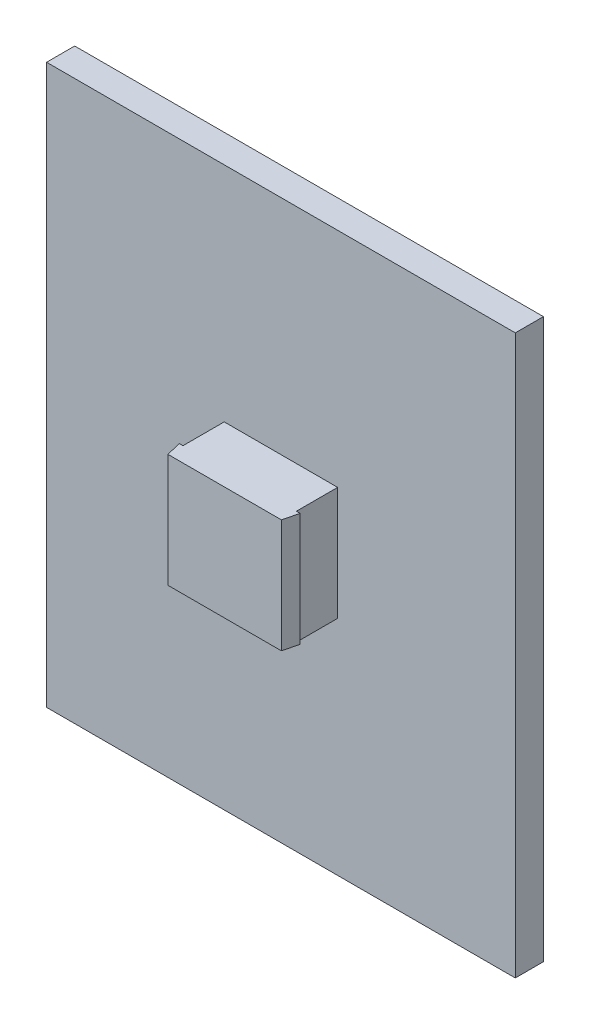
SolidWorks part; units mm, degrees
ref_plane "Front Plane" through (0, 0, 0) normal (1, 0, 0) x (0, 1, 0)
ref_plane "Top Plane" through (0, 0, 0) normal (0, 0, 1) x (0, 1, 0)
ref_plane "Right Plane" through (0, 0, 0) normal (0, 1, 0) x (-1, 0, 0)
sketch "Sketch2" plane through (0, 0, 0) normal (0, 0, 1) x (0, 1, 0)
  line L1 (-14.9, -12.5) -> (14.9, -12.5)
  line L2 (-14.9, -12.5) -> (-14.9, 12.5)
  line L3 (-14.9, 12.5) -> (14.9, 12.5)
  line L4 (14.9, -12.5) -> (14.9, 12.5)
  line L5 (-14.9, -12.5) -> (14.9, 12.5) construction
  line L6 (-14.9, 12.5) -> (14.9, -12.5) construction
  point P0 (0, 0)
  dimension "D2" = 25
  dimension "D1" = 29.8
extrude "Boss-Extrude1" add sketch "Sketch2" along normal blind 1.5
sketch "Sketch3" plane through (0, 0, 1.5) normal (0, 0, 1) x (1, 0, 0)
  line L1 (-3.025, -3.025) -> (3.025, -3.025)
  line L2 (-3.025, -3.025) -> (-3.025, 3.025)
  line L3 (-3.025, 3.025) -> (3.025, 3.025)
  line L4 (3.025, -3.025) -> (3.025, 3.025)
  line L5 (-3.025, -3.025) -> (3.025, 3.025) construction
  line L6 (-3.025, 3.025) -> (3.025, -3.025) construction
  point P0 (0, 0)
  dimension "D1" = 6.05
extrude "Boss-Extrude2" add sketch "Sketch3" along normal blind 3 contours L3 L4 L1 L2
sketch "Sketch4" plane through (0, 3.025, 0) normal (0, 1, 0) x (-1, 0, 0)
  line L0 (-3.025, 4.5) -> (-3.025, 3.7)
  line L1 (-3.025, 4.5) -> (-3.025, 1.5) construction
  line L2 (-3.025, 3.7) -> (-3.225, 3.7)
  line L3 (-3.225, 3.7) -> (-3.025, 4.5)
  line L4 (0, 5.2406) -> (0, -0.8054) construction
  line L5 (3.225, 3.7) -> (3.025, 4.5)
  line L6 (3.025, 3.7) -> (3.225, 3.7)
  line L7 (3.025, 4.5) -> (3.025, 3.7)
  dimension "D1" = 0.8
  dimension "D2" = 0.2
extrude "Boss-Extrude3" add sketch "Sketch4" against normal up to surface (6.05 mm away) up to face at (0, -3.025, 3)
equation "\"D1@Sketch3\" = \"Rectangle_Button_Stem_w\" - \"Rectangle_Button_Stem_marge\""
equation "\"D1@Boss-Extrude2\" = \"Rectangle_Button_Stem_Length\""
equation "\"Rectangle_Button_Width\"= 29.8mm"
equation "\"Rectangle_Button_Length\"= 25mm"
equation "\"Rectangle_Button_Stem_w\"= 6.2mm"
equation "\"Rectangle_Button_Stem_Length\"= 3mm"
equation "\"Rectangle_Button_Stem_marge\"= 0.15mm"
equation "\"D2@Sketch2\"=\"Rectangle_Button_Length\""
equation "\"D1@Sketch2\"=\"Rectangle_Button_Width\""
